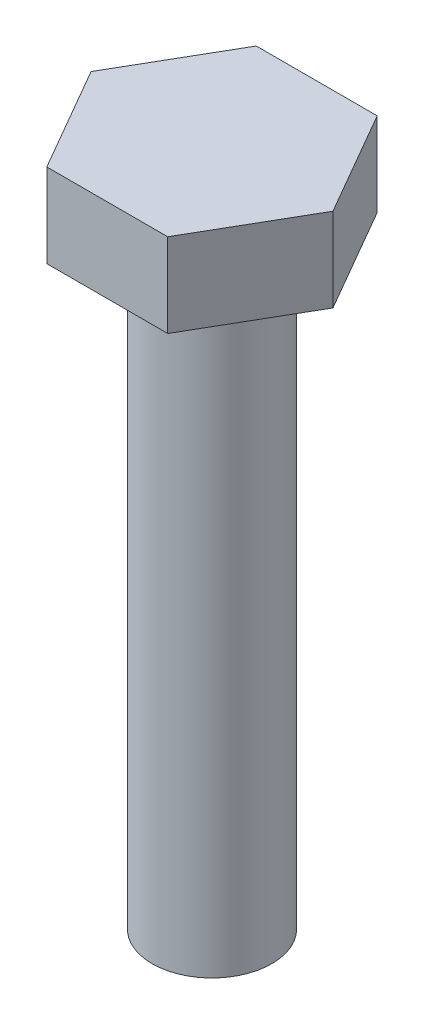
SolidWorks part; units mm, degrees
ref_plane "前视基准面" through (0, 0, 0) normal (0, 0, 1) x (1, 0, 0)
ref_plane "上视基准面" through (0, 0, 0) normal (0, 1, 0) x (1, 0, 0)
ref_plane "右视基准面" through (0, 0, 0) normal (1, 0, 0) x (0, 0, -1)
sketch "草图1" plane through (0, 0, 0) normal (0, 1, 0) x (1, 0, 0)
  circle A0 centre (0, 0) radius 2
  dimension "D1" = 4
extrude "凸台-拉伸1" add sketch "草图1" along normal blind 20
sketch "草图2" plane through (0, 20, 0) normal (0, 1, 0) x (1, 0, 0)
  line L1 (4.0415, 0) -> (2.0207, 3.5)
  line L2 (2.0207, 3.5) -> (-2.0207, 3.5)
  line L3 (-2.0207, 3.5) -> (-4.0415, 0)
  line L4 (-4.0415, 0) -> (-2.0207, -3.5)
  line L5 (-2.0207, -3.5) -> (2.0207, -3.5)
  line L6 (2.0207, -3.5) -> (4.0415, 0)
  circle A0 centre (0, 0) radius 3.5 construction
  dimension "D1" = 7
extrude "凸台-拉伸2" add sketch "草图2" along normal blind 2.8
